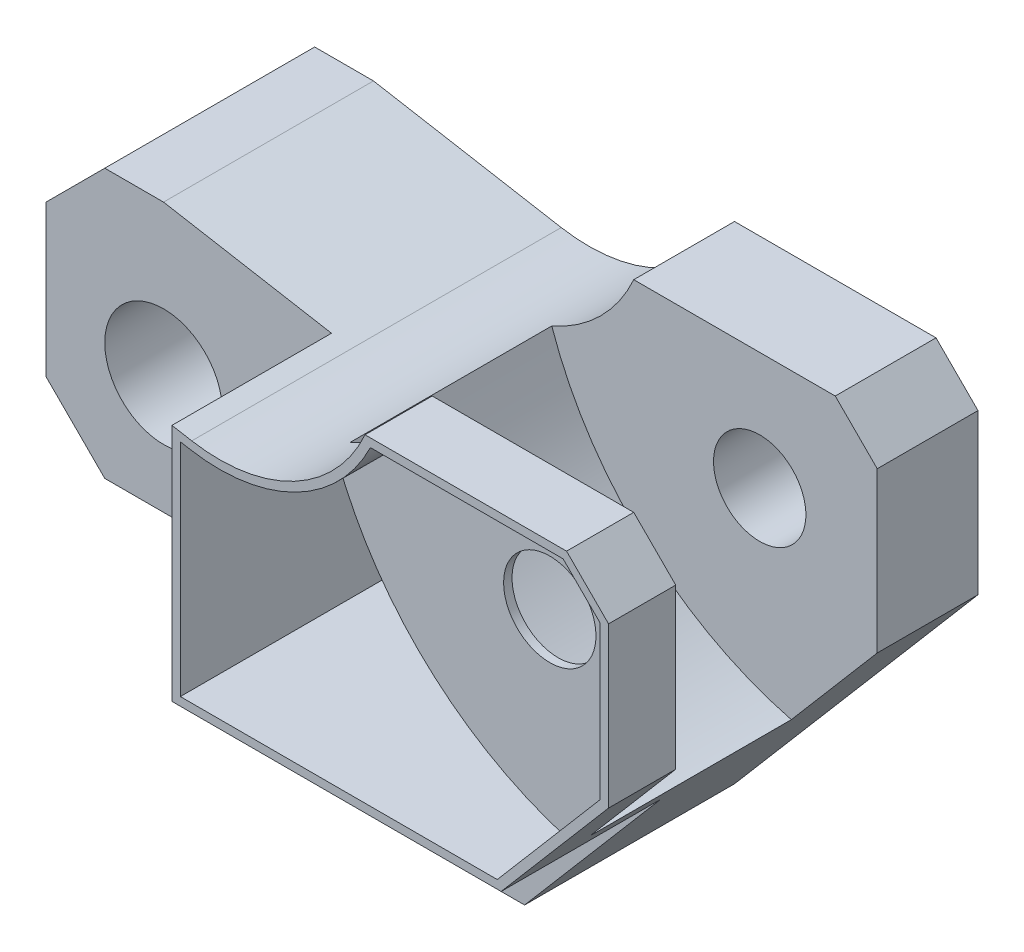
SolidWorks part; units mm, degrees
material "AISI 1020"
ref_plane "Plan de face" through (0, 0, 0) normal (0, 0, 1) x (1, 0, 0)
ref_plane "Plan de dessus" through (0, 0, 0) normal (0, 1, 0) x (1, 0, 0)
ref_plane "Plan de droite" through (0, 0, 0) normal (1, 0, 0) x (0, 0, -1)
sketch "Esquisse1" plane through (0, 0, 0) normal (0, 0, 1) x (1, 0, 0)
  line L0 (-14, 18) -> (0, 18)
  line L1 (72, -33) -> (-14, -33) construction
  line L2 (72, -33) -> (72, 25) construction
  line L3 (72, 25) -> (-14, 25) construction
  line L4 (-14, -33) -> (-14, 25) construction
  line L5 (0, 18) -> (22.3614, 14.0571)
  line L6 (43, 25) -> (67, 25)
  line L7 (67, 25) -> (72, 25)
  line L8 (72, 25) -> (72, 1)
  line L9 (72, 1) -> (43, -33)
  line L10 (43, -33) -> (37.297, -33)
  line L12 (25.5755, -14) -> (-14, -14)
  line L13 (-14, -14) -> (-14, 18)
  circle A0 centre (0, 0) radius 7
  arc A1 (22.3614, 14.0571) -> (43, 25) centre (25.6607, 32.7684) ccw
  arc A2 (37.297, -33) -> (30.5212, -18.2647) centre (59.2059, -14) cw
  arc A3 (30.5212, -18.2647) -> (25.5755, -14) centre (25.5755, -19) ccw
  circle A4 centre (58, 11) radius 5.5
  dimension "D13" = 5
  dimension "D14" = 29
  dimension "D9" = 19
  dimension "D18" = 14
  dimension "D1" = 86
  dimension "D2" = 58
  dimension "D4" = 24
  dimension "D5" = 14
  dimension "D6" = 14
  dimension "D7" = 32
  dimension "D8" = 19
  dimension "D12" = 10
  dimension "D15" = 29
  dimension "D16" = 14
  dimension "D17" = 19
  dimension "D3" = 29
  dimension "D10" = 14
  dimension "D11" = 14
extrude "Boss.-Extru.1" add sketch "Esquisse1" along normal blind 44
chamfer "Chanfrein1" distance 7 angle 45 2 edges at (-14, -14, 22) (-14, 18, 22)
chamfer "Chanfrein2" distance 5 angle 45 1 edges at (72, 25, 22)
sketch "Esquisse2" plane through (0, 25, 0) normal (0, 1, 0) x (1, 0, 0)
  line L0 (-14, -44) -> (-14, -25)
  line L1 (-14, -44) -> (-14, 0) construction
  line L2 (-14, -25) -> (20, -25)
  line L3 (20, -25) -> (20, -44)
  line L4 (22.3614, -44) -> (0, -44) construction
  line L5 (-14, -44) -> (20, -44)
  dimension "D1" = 19
  dimension "D2" = 34
extrude "Enlèv. mat.-Extru.1" cut sketch "Esquisse2" against normal through all
sketch "Esquisse4" plane through (72, 0, 0) normal (1, 0, 0) x (0, 0, -1)
  line L1 (-44, -33) -> (-25, -33)
  line L2 (-44, -33) -> (-44, -14)
  line L3 (-44, -14) -> (-25, -14)
  line L4 (-25, -33) -> (-25, -14)
  dimension "D1" = 19
  dimension "D2" = 19
extrude "Enlèv. mat.-Extru.2" cut sketch "Esquisse4" against normal through all contours L2 L1 L4 L3
sketch "Esquisse5" plane through (0, 0, 0) normal (0, 0, -1) x (-1, 0, 0)
  line L11 (-43, 25) -> (-67, 25)
  line L12 (-67, 25) -> (-72, 20)
  line L13 (-72, 20) -> (-72, 1)
  line L14 (-72, 1) -> (-43, -33)
  line L15 (-43, -33) -> (-37.297, -33)
  line L16 (-25.5755, -14) -> (7, -14)
  line L17 (7, -14) -> (14, -7)
  line L18 (14, -7) -> (14, 11)
  line L19 (14, 11) -> (7, 18)
  line L20 (7, 18) -> (0, 18)
  line L21 (0, 18) -> (-22.3614, 14.0571)
  line L22 (-43, 25) -> (-67, 25)
  line L23 (-67, 25) -> (-72, 20)
  line L24 (-72, 20) -> (-72, 1)
  line L25 (-72, 1) -> (-61.7647, -11)
  arc A0 (-61.7647, -11) -> (-33.2369, 15.3443) centre (-72, 28.7019) ccw
  arc A4 (-37.297, -33) -> (-30.5212, -18.2647) centre (-59.2059, -14) ccw
  arc A5 (-25.5755, -14) -> (-30.5212, -18.2647) centre (-25.5755, -19) ccw
  arc A6 (-43, 25) -> (-22.3614, 14.0571) centre (-25.6607, 32.7684) ccw
  arc A9 (-43, 25) -> (-33.2369, 15.3443) centre (-25.6607, 32.7684) ccw
  dimension "D2" = 41
  dimension "D3" = 36
  dimension "D1" = 0
extrude "Enlèv. mat.-Extru.3" cut sketch "Esquisse5" against normal blind 24 from offset 12 contours L22 L23 L24 L25 A0 A9 offset against normal yes
sketch "Esquisse7" plane through (0, 0, 44) normal (0, 0, 1) x (1, 0, 0)
  line L14 (21, -13) -> (58.7445, -13)
  line L15 (58.7445, -13) -> (71, 1.3685)
  line L16 (71, 1.3685) -> (71, 19.5858)
  line L17 (71, 19.5858) -> (66.5858, 24)
  line L18 (66.5858, 24) -> (43.6361, 24)
  line L19 (22.1877, 13.0723) -> (21, 13.2817)
  line L20 (21, 13.2817) -> (21, -13)
  line L21 (21, -13) -> (58.7445, -13)
  line L22 (58.7445, -13) -> (71, 1.3685)
  line L23 (71, 1.3685) -> (71, 19.5858)
  line L24 (71, 19.5858) -> (66.5858, 24)
  line L25 (66.5858, 24) -> (43.6361, 24)
  line L26 (22.1877, 13.0723) -> (21, 13.2817)
  line L27 (21, 13.2817) -> (21, -13)
  arc A2 (22.1877, 13.0723) -> (43.6361, 24) centre (25.6607, 32.7684) ccw
  arc A3 (22.1877, 13.0723) -> (43.6361, 24) centre (25.6607, 32.7684) ccw
  dimension "D1" = 1
extrude "Enlèv. mat.-Extru.4" cut sketch "Esquisse7" against normal offset from surface (7 mm away) 1 up to face at (52.5, 11, 36)
sketch "Esquisse8" plane through (0, 0, 37) normal (0, 0, 1) x (1, 0, 0)
  line L7 (21, 13.2817) -> (21, -13)
  line L8 (21, -13) -> (58.7445, -13)
  line L9 (58.7445, -13) -> (71, 1.3685)
  line L10 (71, 1.3685) -> (71, 19.5858)
  line L11 (71, 19.5858) -> (66.5858, 24)
  line L12 (66.5858, 24) -> (43.6361, 24)
  line L13 (22.1877, 13.0723) -> (21, 13.2817)
  line L14 (21, 13.2817) -> (21, -13)
  line L15 (21, -13) -> (58.7445, -13)
  line L16 (58.7445, -13) -> (59.9868, -11.5434)
  line L20 (22.1877, 13.0723) -> (21, 13.2817)
  arc A2 (32.2915, 15.0185) -> (61.5151, -11.9683) centre (72, 28.7019) ccw
  arc A3 (32.6467, 14.0282) -> (59.9868, -11.5434) centre (72, 28.7019) ccw
  arc A4 (22.1877, 13.0723) -> (43.6361, 24) centre (25.6607, 32.7684) ccw
  arc A5 (22.1877, 13.0723) -> (32.6467, 14.0282) centre (25.6607, 32.7684) ccw
  dimension "D1" = 1
  dimension "D2" = 0
extrude "Enlèv. mat.-Extru.5" cut sketch "Esquisse8" against normal offset from surface (25 mm away) 12 up to face at (7, 0, 0)
equation "\"A\"= 86"
equation "\"B\"= 58"
equation "\"C\"= 44"
equation "\"D1@Boss.-Extru.1\"=\"C\""
equation "\"D1@Esquisse1\"=\"A\""
equation "\"D2@Esquisse1\"=\"B\""
equation "\"D2@Esquisse2\"=\"A\" - 52"
